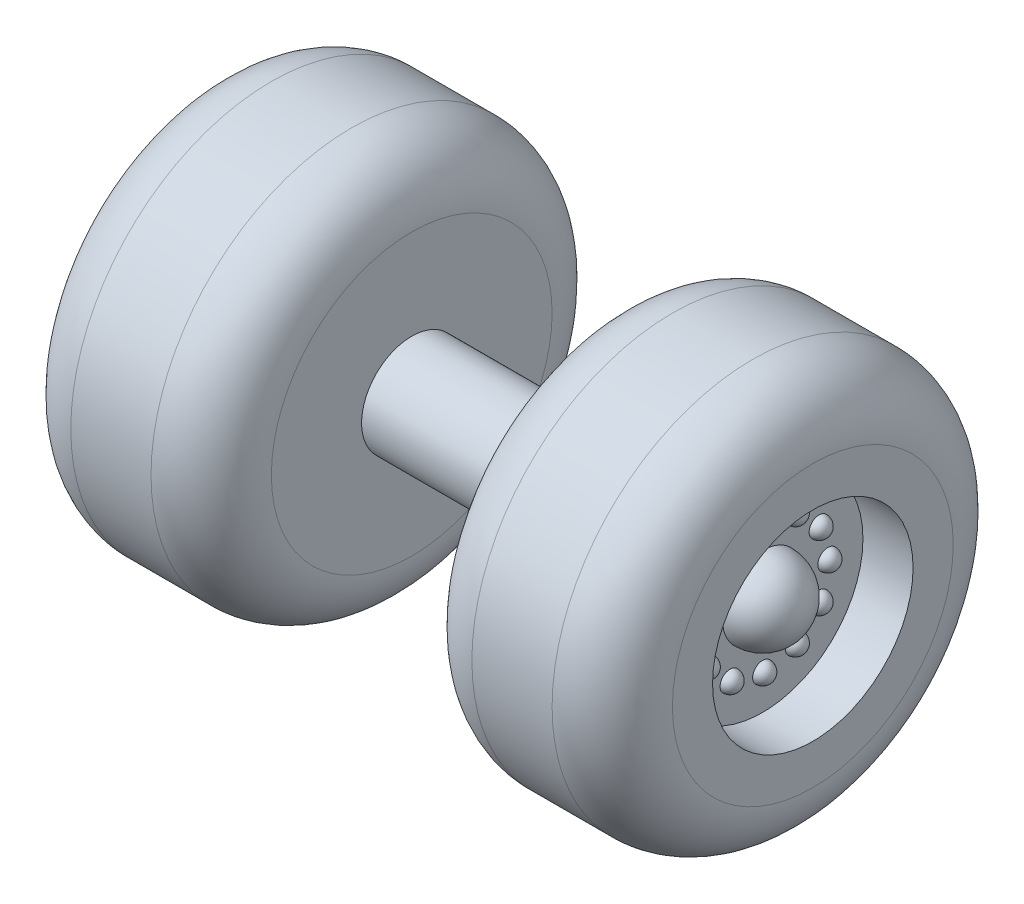
SolidWorks part; units mm, degrees
ref_plane "Front Plane" through (0, 0, 0) normal (0, 0, 1) x (1, 0, 0)
ref_plane "Top Plane" through (0, 0, 0) normal (0, 1, 0) x (1, 0, 0)
ref_plane "Right Plane" through (0, 0, 0) normal (1, 0, 0) x (0, 0, -1)
sketch "Sketch1" plane through (0, 0, 0) normal (1, 0, 0) x (0, 0, -1)
  line L0 (0, 6.35) -> (0, -6.35) construction
  circle A0 centre (0, 0) radius 6.35
  dimension "D1" = 12.7
extrude "Boss-Extrude1" add sketch "Sketch1" along normal blind 25.4
sketch "Sketch2" plane through (0, 0, 0) normal (1, 0, 0) x (0, 0, -1)
  line L0 (0, 25.4) -> (0, -25.4) construction
  circle A0 centre (0, 0) radius 25.4
  dimension "D1" = 50.8
extrude "Boss-Extrude2" add sketch "Sketch2" against normal blind 25.4
ref_plane "Plane1" through (12.7, 0, 0) normal (1, 0, 0) x (0, 0, -1)
ref_plane "Plane3" through (-25.4, 0, 0) normal (1, 0, 0) x (0, 0, -1)
sketch "Sketch3" plane through (-25.4, 0, 0) normal (1, 0, 0) x (0, 0, -1)
  line L0 (12.7, 0) -> (-12.7, 0) construction
  circle A0 centre (0, 0) radius 12.7
  dimension "D1" = 25.4
extrude "Cut-Extrude1" cut sketch "Sketch3" along normal blind 6.35
sketch "Sketch4" plane through (-19.05, 0, 0) normal (-1, 0, 0) x (0, 0, 1)
  line L0 (-5.08, 0) -> (5.08, 0) construction
  line L1 (-5.08, 0) -> (5.08, 0)
  arc A0 (5.08, 0) -> (-5.08, 0) centre (0, 0) ccw
  dimension "D1" = 10.16
revolve "Revolve1" add sketch "Sketch4" angle 180 about L0
sketch "Sketch5" plane through (-19.05, 0, 0) normal (-1, 0, 0) x (0, 0, 1)
  line L0 (-9.525, 0) -> (-6.985, 0) construction
  line L1 (-9.525, 0) -> (-6.985, 0)
  arc A0 (-6.985, 0) -> (-9.525, 0) centre (-8.255, 0) ccw
  dimension "D1" = 2.54
  dimension "D2" = 8.255
revolve "Revolve2" add sketch "Sketch5" angle 180 about L0
pattern_circular "CirPattern2" count 12 over 360 about axis through (0, 0, 0) along (1, 0, 0) of "Revolve2"
mirror "Mirror1" about plane through (12.7, 0, 0) normal (1, 0, 0) of "Revolve1", "CirPattern2", "Cut-Extrude1", "Boss-Extrude2", "Revolve2"
fillet "Fillet1" radius 7.62 1 edges at (-25.4, 0, -25.4)
fillet "Fillet2" radius 7.62 1 edges at (0, 0, -25.4)
fillet "Fillet3" radius 7.62 1 edges at (50.8, 0, -25.4)
fillet "Fillet4" radius 7.62 1 edges at (25.4, 0, -25.4)
